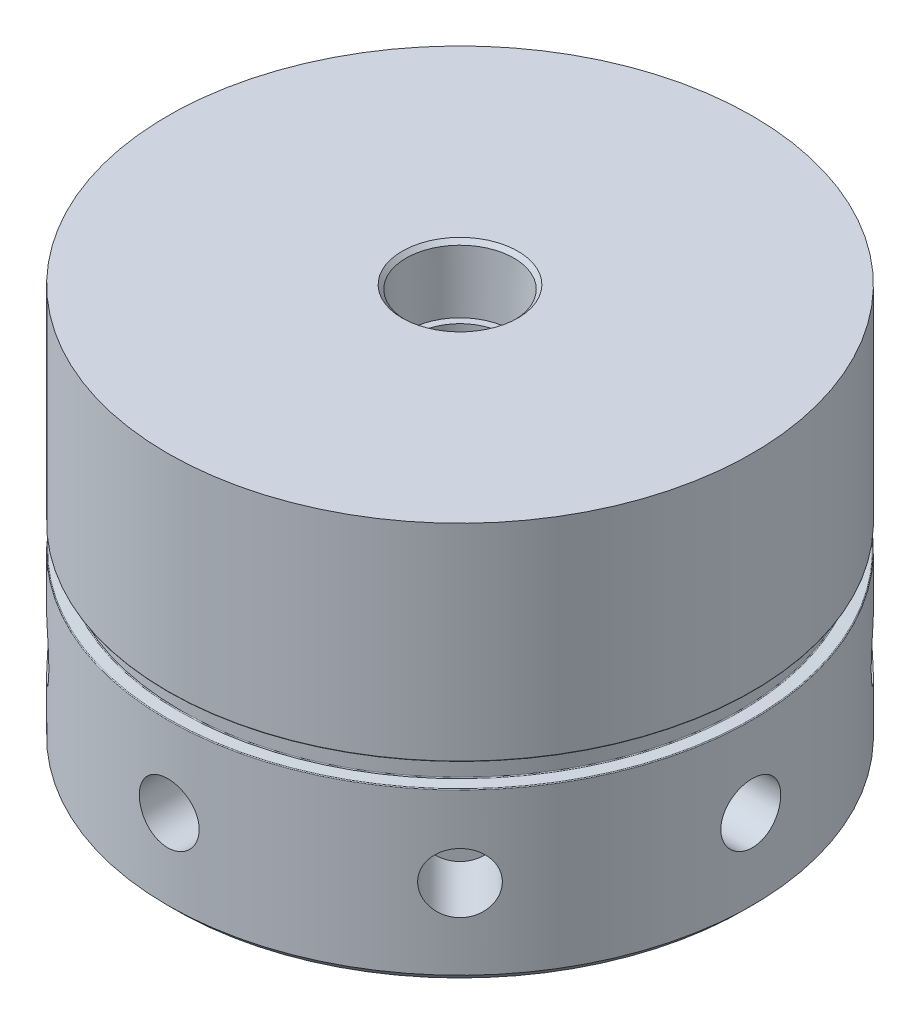
SolidWorks part; units mm, degrees
ref_plane "Front Plane" through (0, 0, 0) normal (0, 0, 1) x (1, 0, 0)
ref_plane "Top Plane" through (0, 0, 0) normal (0, 1, 0) x (1, 0, 0)
ref_plane "Right Plane" through (0, 0, 0) normal (1, 0, 0) x (0, 0, -1)
sketch "Sketch1" plane through (0, 0, 0) normal (0, 0, 1) x (1, 0, 0)
  line L0 (0, 32.1894) -> (0, -38.988) construction
  line L1 (0, -33.4044) -> (-46.4693, -33.4044)
  line L2 (-46.4693, -33.4044) -> (-46.4693, -6.5207)
  line L3 (-46.4693, -6.5207) -> (-44.4373, -6.4142)
  line L4 (-44.4373, -6.4142) -> (-44.4373, -2.8582)
  line L5 (-44.4373, -2.8582) -> (-46.4693, -2.7517)
  line L6 (-46.4693, -2.7517) -> (-46.4693, 30.0956)
  line L7 (-46.4693, 30.0956) -> (0, 30.0956)
  line L8 (0, 30.0956) -> (0, -33.4044)
  dimension "D1" = 92.9386
  dimension "D2" = 92.9386
  dimension "D3" = 88.8746
  dimension "D4" = 93
  dimension "D5" = 93
  dimension "D6" = 3.556
  dimension "D7" = 63.5
revolve "Revolve3" add sketch "Sketch1" angle 360 about L0
fillet "Fillet1" radius 0.127 2 edges at (0, -6.5207, 46.4693) (0, -2.7517, 46.4693)
fillet "Fillet2" radius 0.127 2 edges at (0, -2.8582, 44.4373) (0, -6.4142, 44.4373)
hole_wizard "3/8 NPT Tapped Hole2" positions "Sketch9" profile "Sketch10" size "3/8" standard "ANSI Inch" end condition through all
sketch "Sketch9" plane through (0, 30.0956, 0) normal (0, 1, 0) x (1, 0, 0)
  point P0 (0, 0)
sketch "Sketch10" plane through (0, 30.0956, 0) normal (1, 0, 0) x (0, 0, 1)
  line L0 (0, 0) -> (0, 63.5)
  line L1 (0, 63.5) -> (7.1374, 63.5)
  line L3 (7.1374, 63.5) -> (7.1374, 10.414)
  line L4 (7.1374, 10.414) -> (8.2697, 10.414)
  line L5 (8.2697, 10.414) -> (8.5751, 0.6324)
  line L6 (8.5751, 0.6324) -> (9.2075, 0)
  line L7 (9.2075, 0) -> (0, 0)
  line L8 (0, -6.35) -> (0, 107.95) construction
  line L9 (-8.5751, 0.6324) -> (-9.2075, 0) construction
  line L11 (-7.1374, 10.414) -> (-8.2697, 10.414) construction
  line L12 (-8.2697, 10.414) -> (-8.5751, 0.6324) construction
  dimension "Thru Tap Drill Dia." = 14.2748
  dimension "Thru Tap Drill Depth" = 63.5
  dimension "Thread Dia." = 17.1502
  dimension "Thread Angle" = 3.576
  dimension "Thread Depth" = 10.414
  dimension "Near C'Sink Dia." = 18.415
  dimension "Near C'Sink Angle" = 90
cosmetic thread "Cosmetic Thread1" parameters "D2"=22.225
fillet "Fillet3" radius 0.254 1 edges at (0, -33.4044, 7.1374)
chamfer "Chamfer1" distance 1.27 angle 45 1 edges at (0, -33.4044, 46.4693)
ref_plane "Plane2" through (-46.4693, 0, 0) normal (1, 0, 0) x (0, 0, -1)
sketch "Sketch12" plane through (-46.4693, 0, 0) normal (1, 0, 0) x (0, 0, -1)
  line L0 (0, 33.44) -> (0, -38.7515) construction
  line L1 (46.4693, -32.1344) -> (-46.4693, -32.1344) construction
  circle A0 centre (0, -19.4344) radius 4.7625
  dimension "D1" = 9.525
  dimension "D2" = 12.7
extrude "Cut-Extrude3" cut sketch "Sketch12" along normal blind 10.922
pattern_circular "CirPattern1" count 8 over 360 about axis through (0, 0, 0) along (0, 1, 0) of "Cut-Extrude3"
